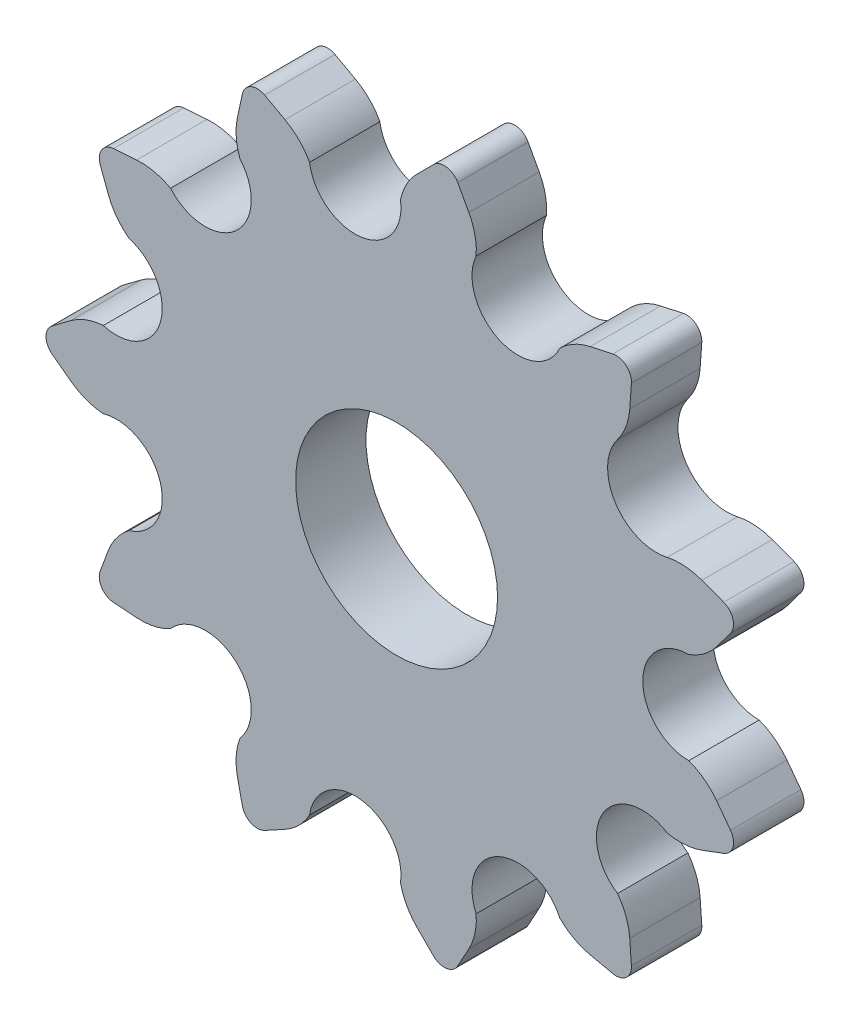
SolidWorks part; units mm, degrees
ref_plane "Front Plane" through (0, 0, 0) normal (0, 0, 1) x (1, 0, 0)
ref_plane "Top Plane" through (0, 0, 0) normal (0, 1, 0) x (1, 0, 0)
ref_plane "Right Plane" through (0, 0, 0) normal (1, 0, 0) x (0, 0, -1)
sketch "Sketch1" plane through (0, 0, 0) normal (0, 0, 1) x (1, 0, 0)
  line L0 (8.0371, 10.9326) -> (8.9778, 11.1372)
  line L1 (0.8506, 13.5422) -> (1.5314, 14.223)
  line L2 (9.6775, 9.5111) -> (9.7462, 10.4714)
  line L3 (2.9991, 13.2333) -> (2.5377, 14.0783)
  line L4 (12.6718, 4.8519) -> (13.5738, 4.5154)
  line L5 (13.2833, 2.7692) -> (13.8603, 3.5399)
  line L6 (13.2833, -2.7692) -> (13.8603, -3.5399)
  line L7 (12.6718, -4.8519) -> (13.5738, -4.5154)
  line L8 (9.6775, -9.5111) -> (9.7462, -10.4714)
  line L9 (8.0371, -10.9326) -> (8.9778, -11.1372)
  line L10 (2.9991, -13.2333) -> (2.5377, -14.0783)
  line L11 (0.8506, -13.5422) -> (1.5314, -14.223)
  line L13 (-4.6315, -12.754) -> (-5.4764, -13.2154)
  line L14 (-6.6059, -11.8523) -> (-6.4012, -12.7931)
  line L15 (-10.7916, -8.2254) -> (-11.7519, -8.1567)
  line L16 (-11.9651, -6.3994) -> (-12.3015, -7.3014)
  line L17 (-13.5255, -1.0853) -> (-14.2962, -0.5083)
  line L18 (-13.5255, 1.0853) -> (-14.2962, 0.5083)
  line L19 (-11.9651, 6.3994) -> (-12.3015, 7.3014)
  line L20 (-10.7916, 8.2254) -> (-11.7519, 8.1567)
  line L21 (-6.6059, 11.8523) -> (-6.4012, 12.7931)
  line L22 (-4.6315, 12.754) -> (-5.4764, 13.2154)
  circle A0 centre (0, 0) radius 4.191
  arc A1 (3.3024, 11.8226) -> (2.9991, 13.2333) centre (0.7698, 12.016) ccw
  arc A2 (3.3024, 11.8226) -> (6.7723, 10.238) centre (5.0374, 11.0303) ccw
  arc A3 (0.1622, 12.2741) -> (-3.6136, 11.7312) centre (-1.7257, 12.0027) cw
  arc A4 (-6.4995, 10.4133) -> (-9.3823, 7.9153) centre (-7.9409, 9.1643) cw
  arc A5 (-11.0976, 5.2463) -> (-12.1723, 1.5863) centre (-11.6349, 3.4163) cw
  arc A6 (-11.0976, -5.2463) -> (-12.1723, -1.5863) centre (-11.6349, -3.4163) ccw
  arc A7 (-6.4995, -10.4133) -> (-9.3823, -7.9153) centre (-7.9409, -9.1643) ccw
  arc A8 (0.1622, -12.2741) -> (-3.6136, -11.7312) centre (-1.7257, -12.0027) ccw
  arc A9 (3.3024, -11.8226) -> (6.7723, -10.238) centre (5.0374, -11.0303) cw
  arc A10 (11.2323, -4.9513) -> (9.17, -8.1604) centre (10.2011, -6.5559) ccw
  arc A11 (12.1261, -1.9073) -> (12.1261, 1.9073) centre (12.1261, 0) cw
  arc A12 (9.17, 8.1604) -> (11.2323, 4.9513) centre (10.7908, 6.9348) ccw
  arc A13 (0.1622, 12.2741) -> (0.8506, 13.5422) centre (2.6467, 11.7462) cw
  arc A14 (1.5314, 14.223) -> (2.5377, 14.0783) centre (1.9804, 13.774) cw
  arc A15 (9.17, 8.1604) -> (9.6775, 9.5111) centre (7.144, 9.6924) ccw
  arc A16 (6.7723, 10.238) -> (8.0371, 10.9326) centre (8.577, 8.4506) cw
  arc A17 (8.9778, 11.1372) -> (9.7462, 10.4714) centre (9.1128, 10.5167) cw
  arc A18 (12.1261, 1.9073) -> (13.2833, 2.7692) centre (11.25, 4.2914) ccw
  arc A19 (11.2323, 4.9513) -> (12.6718, 4.8519) centre (11.7842, 2.472) cw
  arc A20 (13.5738, 4.5154) -> (13.8603, 3.5399) centre (13.3519, 3.9205) cw
  arc A21 (11.2323, -4.9513) -> (12.6718, -4.8519) centre (11.7842, -2.472) ccw
  arc A22 (12.1261, -1.9073) -> (13.2833, -2.7692) centre (11.25, -4.2914) cw
  arc A23 (13.8603, -3.5399) -> (13.5738, -4.5154) centre (13.3519, -3.9205) cw
  arc A24 (6.7723, -10.238) -> (8.0371, -10.9326) centre (8.577, -8.4506) ccw
  arc A25 (9.17, -8.1604) -> (9.6775, -9.5111) centre (7.144, -9.6924) cw
  arc A26 (9.7462, -10.4714) -> (8.9778, -11.1372) centre (9.1128, -10.5167) cw
  arc A27 (0.1622, -12.2741) -> (0.8506, -13.5422) centre (2.6467, -11.7462) ccw
  arc A28 (3.3024, -11.8226) -> (2.9991, -13.2333) centre (0.7698, -12.016) cw
  arc A29 (2.5377, -14.0783) -> (1.5314, -14.223) centre (1.9804, -13.774) cw
  arc A30 (-6.4995, -10.4133) -> (-6.6059, -11.8523) centre (-4.1239, -11.3124) ccw
  arc A31 (-3.6136, -11.7312) -> (-4.6315, -12.754) centre (-5.8488, -10.5247) cw
  arc A32 (-5.4764, -13.2154) -> (-6.4012, -12.7931) centre (-5.7808, -12.6581) cw
  arc A33 (-11.0976, -5.2463) -> (-11.9651, -6.3994) centre (-9.5852, -7.2871) ccw
  arc A34 (-9.3823, -7.9153) -> (-10.7916, -8.2254) centre (-10.6104, -5.6919) cw
  arc A35 (-11.7519, -8.1567) -> (-12.3015, -7.3014) centre (-11.7066, -7.5234) cw
  arc A36 (-12.1723, 1.5863) -> (-13.5255, 1.0853) centre (-12.0033, -0.9481) ccw
  arc A37 (-12.1723, -1.5863) -> (-13.5255, -1.0853) centre (-12.0033, 0.9481) cw
  arc A38 (-14.2962, -0.5083) -> (-14.2962, 0.5083) centre (-13.9156, 0) cw
  arc A39 (-9.3823, 7.9153) -> (-10.7916, 8.2254) centre (-10.6104, 5.6919) ccw
  arc A40 (-11.0976, 5.2463) -> (-11.9651, 6.3994) centre (-9.5852, 7.2871) cw
  arc A41 (-12.3015, 7.3014) -> (-11.7519, 8.1567) centre (-11.7066, 7.5234) cw
  arc A42 (-3.6136, 11.7312) -> (-4.6315, 12.754) centre (-5.8488, 10.5247) ccw
  arc A43 (-6.4995, 10.4133) -> (-6.6059, 11.8523) centre (-4.1239, 11.3124) cw
  arc A44 (-6.4012, 12.7931) -> (-5.4764, 13.2154) centre (-5.7808, 12.6581) cw
  point P137 (0, 0)
  dimension "D4" = 11
extrude "Boss-Extrude1" add sketch "Sketch1" along normal blind 2.921
